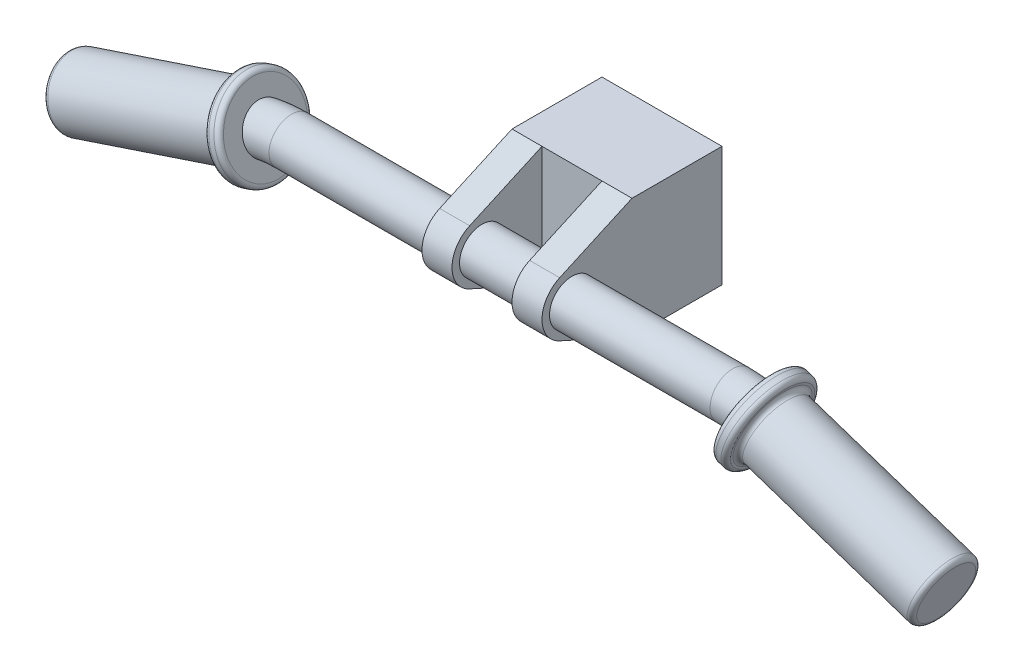
SolidWorks part; units mm, degrees
ref_plane "Front Plane" through (0, 0, 0) normal (0, 0, 1) x (1, 0, 0)
ref_plane "Top Plane" through (0, 0, 0) normal (0, 1, 0) x (1, 0, 0)
ref_plane "Right Plane" through (0, 0, 0) normal (1, 0, 0) x (0, 0, -1)
sketch "Sketch1" plane through (0, 0, 0) normal (0, 0, 1) x (1, 0, 0)
  line L0 (-6.35, 4.7625) -> (9.4615, 4.7625) construction
  line L1 (-1.6192, 3.81) -> (4.7308, 3.81)
  line L2 (-1.6192, 3.81) -> (-1.6192, -2.54)
  line L3 (-1.6192, -2.54) -> (4.7308, -2.54)
  line L4 (4.7308, 3.81) -> (4.7308, -2.54)
  dimension "D1" = 6.35
  dimension "D2" = 6.35
  dimension "D3" = 3.175
  dimension "D4" = 0.9525
extrude "Boss-Extrude1" add sketch "Sketch1" along normal blind 4.7625 contours L4 L3 L2 L1
sketch "Sketch3" plane through (4.7308, 0, 0) normal (1, 0, 0) x (0, 0, -1)
  line L0 (-4.7625, 3.81) -> (-4.7625, -2.54) construction
  line L1 (-4.7625, 3.81) -> (-8.5907, 2.0819)
  line L2 (-4.7625, -2.54) -> (-8.5907, -0.8119)
  line L3 (-4.7625, -2.54) -> (0, -2.54) construction
  line L4 (-4.7625, 3.81) -> (-4.7625, -2.54)
  line L5 (-4.7625, -2.54) -> (-4.7544, -2.5217)
  circle A0 centre (-7.9375, 0.635) radius 1.5875
  line M4 (-4.7625, 3.81) -> (-4.7625, -2.54)
  dimension "D2" = 3.175
  dimension "D1" = 3.175
  dimension "D3" = 3.175
extrude "Boss-Extrude2" add sketch "Sketch3" against normal blind 1.5875 contours A0 | A0 L2 L1 M4
sketch "Sketch4" plane through (-1.6192, 0, 0) normal (-1, 0, 0) x (0, 0, 1)
  line L0 (8.5907, -0.8119) -> (4.7625, -2.54)
  line L1 (4.7625, -2.54) -> (4.7625, 3.81)
  line L2 (4.7625, 3.81) -> (8.5907, 2.0819)
  circle A0 centre (7.9375, 0.635) radius 1.5875
  line M3 (4.7625, -2.54) -> (4.7625, 3.81)
extrude "Boss-Extrude3" add sketch "Sketch4" against normal blind 1.5875 contours A0 L2 L0 M3 | A0
sketch "Sketch5" plane through (-1.6192, 0, 0) normal (-1, 0, 0) x (0, 0, 1)
  circle A0 centre (7.9375, 0.635) radius 1.1906
  dimension "D1" = 2.3813
ref_plane "Plane1" through (0, 0, 7.9375) normal (0, 0, 1) x (1, 0, 0)
sketch "Sketch6" plane through (0, 0, 7.9375) normal (0, 0, 1) x (1, 0, 0)
  line L0 (-1.6192, 0.635) -> (4.7308, 0.635)
  line L1 (-1.6192, 1.8256) -> (-1.6192, -0.5556) construction
  line L2 (4.7308, -0.8119) -> (4.7308, 2.0819) construction
  line L3 (4.7308, 0.635) -> (13.2253, 0.635)
  line L4 (15.2333, 0.3091) -> (23.7808, -2.54)
  line L5 (-1.6192, 0.635) -> (-4.7942, 0.635)
  line L6 (-4.7942, 0.635) -> (-11.1442, -2.54)
  arc A0 (13.2253, 0.635) -> (15.2333, 0.3091) centre (13.2253, -5.715) cw
  point P12 (14.2558, 0.635)
  dimension "D7" = 6.35
  dimension "D1" = 9.525
  dimension "D2" = 9.525
  dimension "D3" = 3.175
  dimension "D4" = 3.175
  dimension "D5" = 6.35
  dimension "D6" = 3.175
sweep "Sweep1" add profiles "Sketch5" path "Sketch6"
ref_plane "Plane2" through (1.5558, 0, 0) normal (-1, 0, 0) x (0, 0, 1)
mirror "Mirror1" about plane through (1.5558, 0, 0) normal (-1, 0, 0) of "Sweep1"
sketch "Sketch7" plane through (22.1647, -7.3882, 0) normal (0.9487, -0.3162, 0) x (0, 0, -1)
  circle A0 centre (-7.9375, 5.1105) radius 1.7463
  dimension "D1" = 3.4925
extrude "Boss-Extrude4" add sketch "Sketch7" along normal blind 0.7937 and the other way blind 8.89
sketch "Sketch8" plane through (13.7309, -4.577, 0) normal (-0.9487, 0.3162, 0) x (0, 0, 1)
  circle A0 centre (7.9375, 5.1105) radius 2.3813
  dimension "D1" = 4.7625
extrude "Boss-Extrude5" add sketch "Sketch8" along normal blind 0.7937
fillet "Fillet2" radius 0.254 1 edges at (25.086, -1.1344, 7.9375)
fillet "Fillet3" radius 0.254 1 edges at (14.7947, -1.3854, 7.9375)
fillet "Fillet4" radius 0.254 2 edges at (13.8409, -1.7368, 7.9375) (14.5939, -1.9878, 7.9375)
mirror "Mirror3" about plane through (1.5558, 0, 0) normal (-1, 0, 0) of "Fillet4", "Fillet3", "Fillet2", "Boss-Extrude5", "Boss-Extrude4"
